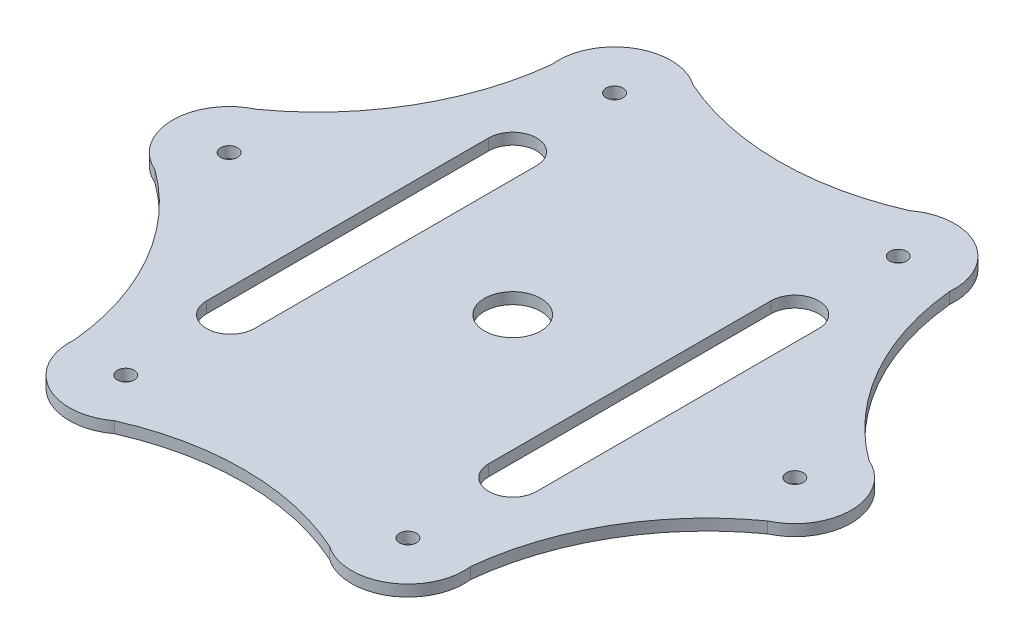
SolidWorks part; units mm, degrees
material "1060 Alloy"
ref_plane "Front Plane" through (0, 0, 0) normal (0, 0, 1) x (1, 0, 0)
ref_plane "Top Plane" through (0, 0, 0) normal (0, 1, 0) x (1, 0, 0)
ref_plane "Right Plane" through (0, 0, 0) normal (1, 0, 0) x (0, 0, -1)
sketch "Sketch1" plane through (0, 0, 0) normal (0, 1, 0) x (1, 0, 0)
  line L4 (0.0837, 94.4377) -> (-0.0837, -94.4377) construction
  line L5 (-113.5778, 0) -> (113.5778, 0) construction
  arc A0 (-34.9638, -42.6911) -> (-19.006, -51.5551) centre (-25.0008, -43.5513) ccw
  arc A1 (-19.006, -51.5551) -> (19.2728, -51.7494) centre (-0.0837, -94.4377) cw
  arc A2 (19.2728, -51.7494) -> (34.9281, -42.3615) centre (24.9992, -43.5513) ccw
  arc A3 (34.9281, -42.3615) -> (54.2366, -9.0582) centre (81.5552, -47.1458) cw
  arc A4 (54.2366, -9.0582) -> (53.9341, 9.1936) centre (50, 0) ccw
  arc A5 (53.9341, 9.1936) -> (35.148, 42.2735) centre (81.7922, 46.8885) cw
  arc A6 (35.148, 42.2735) -> (19.1903, 51.1375) centre (25.1851, 43.1336) ccw
  arc A7 (19.1903, 51.1375) -> (-19.2745, 51.2494) centre (0.0837, 94.4377) cw
  arc A8 (-19.2745, 51.2494) -> (-34.9298, 41.8615) centre (-25.0008, 43.0513) ccw
  arc A9 (-34.9298, 41.8615) -> (-54.2374, 8.8082) centre (-81.5284, 46.9157) cw
  arc A10 (-54.2374, 8.8082) -> (-53.9349, -9.4436) centre (-50.0008, -0.25) ccw
  arc A11 (-53.9349, -9.4436) -> (-34.9638, -42.6911) centre (-81.6112, -47.2721) cw
  circle A16 centre (50, 0) radius 1.5
  circle A17 centre (24.9992, -43.5513) radius 1.5
  circle A18 centre (25.1851, 43.1336) radius 1.5
  circle A19 centre (-25.0008, -43.5513) radius 1.5
  circle A20 centre (-50.0008, -0.25) radius 1.5
  circle A21 centre (-25.0008, 43.0513) radius 1.5
  dimension "D4" = 3
extrude "Boss-Extrude1" add sketch "Sketch1" against normal blind 2
sketch "Sketch2" plane through (0, 0, 0) normal (0, 1, 0) x (1, 0, 0)
  line L0 (0, -53.8004) -> (0, 53.8004) construction
  line L1 (-82.0993, 0) -> (82.0993, 0) construction
  line L2 (-25, 25) -> (-25, -25) construction
  line L3 (-20.75, 25) -> (-20.75, -25)
  line L4 (-29.25, 25) -> (-29.25, -25)
  line L6 (25, 25) -> (25, -25) construction
  line L7 (20.75, 25) -> (20.75, -25)
  line L8 (29.25, 25) -> (29.25, -25)
  arc A0 (-20.75, 25) -> (-29.25, 25) centre (-25, 25) ccw
  arc A1 (-29.25, -25) -> (-20.75, -25) centre (-25, -25) ccw
  arc A2 (20.75, 25) -> (29.25, 25) centre (25, 25) cw
  arc A3 (29.25, -25) -> (20.75, -25) centre (25, -25) cw
  point P4 (0, 0)
  point P8 (0, 0)
  point P10 (-25, 0)
  point P17 (25, 0)
  dimension "D3" = 50
  dimension "D1" = 8.5
  dimension "D2" = 25
extrude "Cut-Extrude1" cut sketch "Sketch2" against normal through all
sketch "Sketch3" plane through (0, 0, 0) normal (0, 1, 0) x (1, 0, 0)
  circle A0 centre (0, 0) radius 5
  dimension "D1" = 10
extrude "Cut-Extrude2" cut sketch "Sketch3" against normal through all
